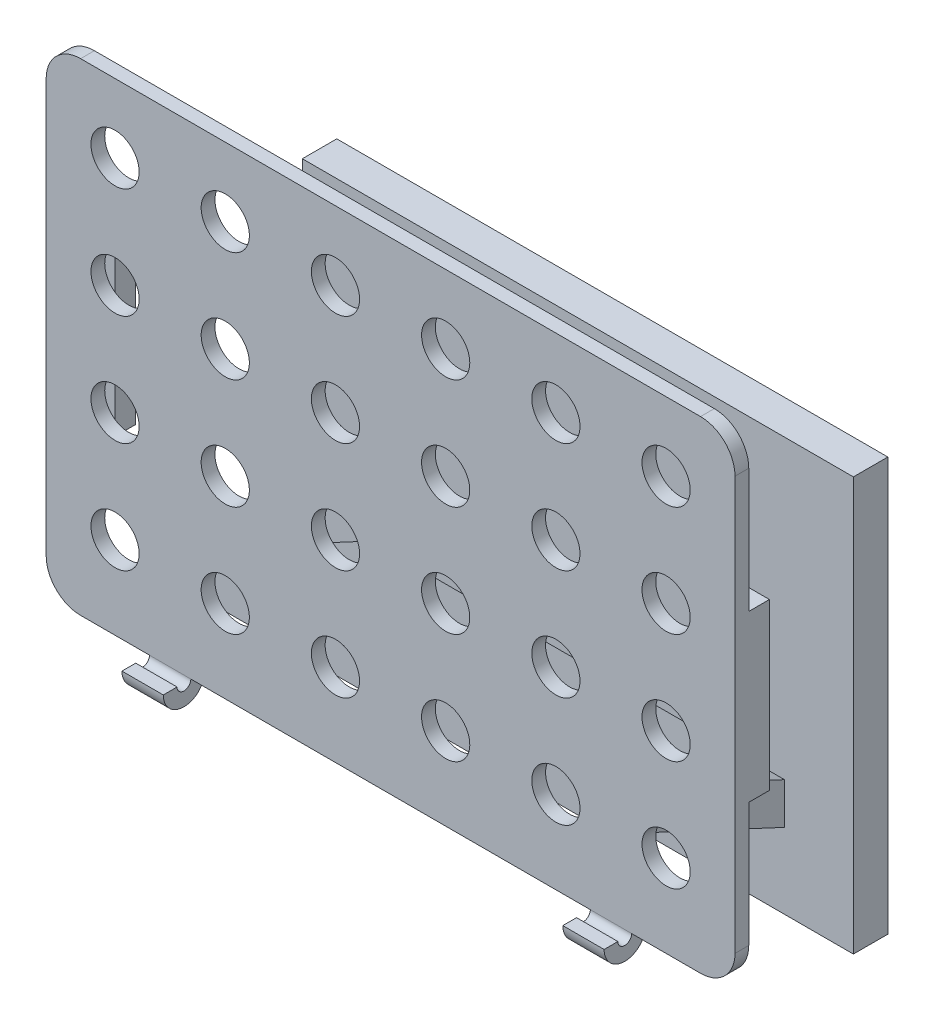
SolidWorks part; units mm, degrees
ref_plane "Front Plane" through (0, 0, 0) normal (0, 0, 1) x (1, 0, 0)
ref_plane "Top Plane" through (0, 0, 0) normal (0, 1, 0) x (1, 0, 0)
ref_plane "Right Plane" through (0, 0, 0) normal (1, 0, 0) x (0, 0, -1)
sketch "Sketch1" plane through (0, 0, 0) normal (0, 0, 1) x (1, 0, 0)
  line L1 (-475, 350) -> (-25, 350)
  line L2 (-500, 325) -> (-500, 25)
  line L3 (-475, 0) -> (-25, 0)
  line L4 (0, 325) -> (0, 25)
  arc A0 (-25, 350) -> (0, 325) centre (-25, 325) cw
  arc A1 (0, 25) -> (-25, 0) centre (-25, 25) cw
  arc A2 (-475, 0) -> (-500, 25) centre (-475, 25) cw
  arc A3 (-500, 325) -> (-475, 350) centre (-475, 325) cw
  point P7 (0, 350)
  point P10 (0, 0)
  point P15 (-500, 350)
  dimension "D3" = 25
  dimension "D1" = 500
  dimension "D2" = 350
extrude "Boss-Extrude1" add sketch "Sketch1" along normal blind 10
sketch "Sketch2" plane through (0, 0, 0) normal (0, -1, 0) x (1, 0, 0)
  line L0 (-250, 10) -> (-250, 0) construction
  line L1 (-475, 10) -> (-25, 10) construction
  line L2 (-475, 0) -> (-25, 0) construction
  line L3 (-475, 10) -> (-475, 0) construction
  line L5 (-425, 10) -> (-395, 10)
  line L6 (-425, 10) -> (-425, 0)
  line L7 (-425, 0) -> (-395, 0)
  line L8 (-395, 10) -> (-395, 0)
  point P6 (-475, 5)
  dimension "D1" = 30
  dimension "D2" = 50
ref_plane "Plane1" through (-410, 0, 0) normal (-1, 0, 0) x (0, 0, 1)
sketch "Sketch3" plane through (-410, 0, 0) normal (-1, 0, 0) x (0, 0, 1)
  line L0 (10, 12.5) -> (0, 12.5) construction
  line L1 (10, 0) -> (10, 25) construction
  line L2 (0, 25) -> (0, 0) construction
  line L3 (5, 12.5) -> (5, 0) construction
  arc A0 (5, 0) -> (25, 0) centre (15, 0) ccw
  dimension "D1" = 10
sweep "Sweep1" add profiles "Sketch2" path "Sketch3"
sketch "Sketch6" plane through (-500, 0, 0) normal (-1, 0, 0) x (0, 0, 1)
  line L3 (0, 325) -> (0, 25) construction
  line L5 (-15, 235) -> (0, 235)
  line L6 (-15, 235) -> (-15, 115)
  line L7 (-15, 115) -> (0, 115)
  line L8 (0, 235) -> (0, 115)
  line L9 (-15, 235) -> (0, 115) construction
  line L10 (-15, 115) -> (0, 235) construction
  point P2 (-7.5, 175)
  point P3 (0, 175)
  point P7 (0, 175)
  dimension "D1" = 15
  dimension "D2" = 120
extrude "Boss-Extrude2" add sketch "Sketch6" against normal blind 40
ref_plane "Plane2" through (-250, 0, 0) normal (-1, 0, 0) x (0, 0, 1)
sketch "Sketch7" plane through (0, 0, 0) normal (0, 0, -1) x (-1, 0, 0)
  line L0 (0, 175) -> (500, 175) construction
  line L1 (0, 25) -> (0, 325) construction
  line L2 (500, 235) -> (500, 115) construction
  line L5 (250, -13.75) -> (250, 13.75) construction
  line L6 (400, 75) -> (100, 75)
  line L7 (400, 75) -> (400, 45)
  line L8 (400, 45) -> (100, 45)
  line L9 (100, 75) -> (100, 45)
  line L10 (400, 75) -> (100, 45) construction
  line L11 (400, 45) -> (100, 75) construction
  point P10 (250, 60)
  dimension "D1" = 300
  dimension "D2" = 30
  dimension "D3" = 130
sketch "Sketch8" plane through (-250, 0, 0) normal (-1, 0, 0) x (0, 0, 1)
  line L0 (0, 60) -> (0, 30.8025)
  line L1 (0, 45.4013) -> (-135.9462, -17.9915)
  point P0 (0, 60)
  point P1 (0, 30.8025)
  dimension "D1" = 150
  dimension "D2" = 65
sweep "Sweep2" add profiles "Sketch7" path "Sketch8"
sketch "Sketch9" plane through (-410, 0, 0) normal (-1, 0, 0) x (0, 0, 1)
  line L0 (-135.9462, -18.3927) -> (13.6055, -18.3927) construction
ref_plane "Plane3" through (-400, -18.3927, -135.9462) normal (0, 0, 1) x (1, 0, 0)
sketch "Sketch10" plane through (-400, -18.3927, -135.9462) normal (0, 0, 1) x (1, 0, 0)
  line L0 (-50, -50) -> (350, -50)
  line L1 (-50, -50) -> (-50, 250)
  line L2 (350, -50) -> (350, 250)
  line L3 (-50, 250) -> (350, 250)
  line L4 (350, 250) -> (-50, -50) construction
  line L5 (300, 0) -> (0, 0) construction
  point P0 (150, 100)
  point P7 (150, 0)
  point P10 (134.4557, 49.7215)
  dimension "D1" = 400
  dimension "D2" = 300
  dimension "D3" = 0
  dimension "D4" = 100
extrude "Boss-Extrude3" add sketch "Sketch10" against normal blind 15 and the other way blind 10
sketch "Sketch11" plane through (0, 0, 10) normal (0, 0, 1) x (1, 0, 0)
  line L0 (-492.6777, 342.6777) -> (-7.3223, 7.3223) construction
  line L1 (-7.3223, 342.6777) -> (-492.6777, 7.3223) construction
  line L2 (-250, 175) -> (-250, 0) construction
  line L3 (-395, 0) -> (-25, 0) construction
  line L4 (-250, 13.75) -> (-250, -13.75) construction
  line L5 (-25, 350) -> (-475, 350) construction
  line L6 (-500, 325) -> (-500, 25) construction
  arc A0 (-475, 350) -> (-500, 325) centre (-475, 325) ccw construction
  arc A1 (-25, 0) -> (0, 25) centre (-25, 25) ccw construction
  arc A2 (0, 325) -> (-25, 350) centre (-25, 325) ccw construction
  arc A3 (-500, 25) -> (-475, 0) centre (-475, 25) ccw construction
  circle A4 centre (-450, 300) radius 17.5
  dimension "D3" = 35
  dimension "D1" = 50
  dimension "D2" = 50
extrude "Cut-Extrude1" cut sketch "Sketch11" against normal up to surface (10 mm away) up to face at (-250, 60, 0)
pattern_linear "LPattern1" count 3 spacing 80 along (1, 0, 0) count 4 spacing 80 along (0, -1, 0) of "Cut-Extrude1"
mirror "Mirror1" about plane through (-250, 0, 0) normal (-1, 0, 0) of "Sweep1", "Boss-Extrude2", "LPattern1", "Cut-Extrude1"
